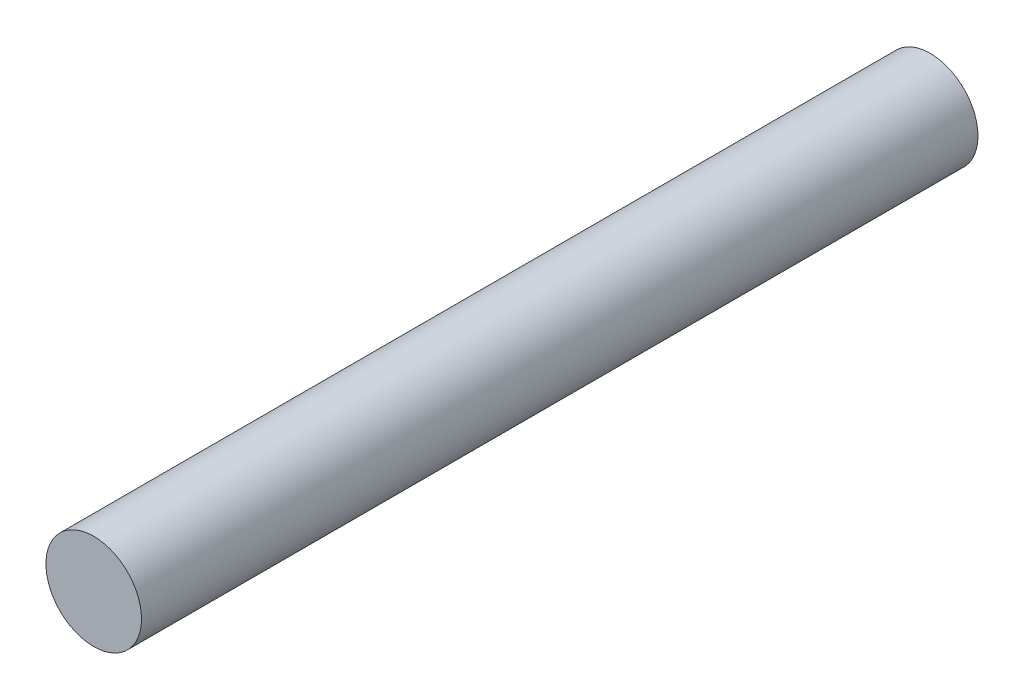
SolidWorks part; units mm, degrees
ref_plane "Front Plane" through (0, 0, 0) normal (0, 0, 1) x (1, 0, 0)
ref_plane "Top Plane" through (0, 0, 0) normal (0, 1, 0) x (1, 0, 0)
ref_plane "Right Plane" through (0, 0, 0) normal (1, 0, 0) x (0, 0, -1)
sketch "Sketch1" plane through (0, 0, 0) normal (0, 0, 1) x (1, 0, 0)
  circle A0 centre (0, 0) radius 0.4
  dimension "D1" = 0.8
extrude "Boss-Extrude1" add sketch "Sketch1" along normal blind 7
